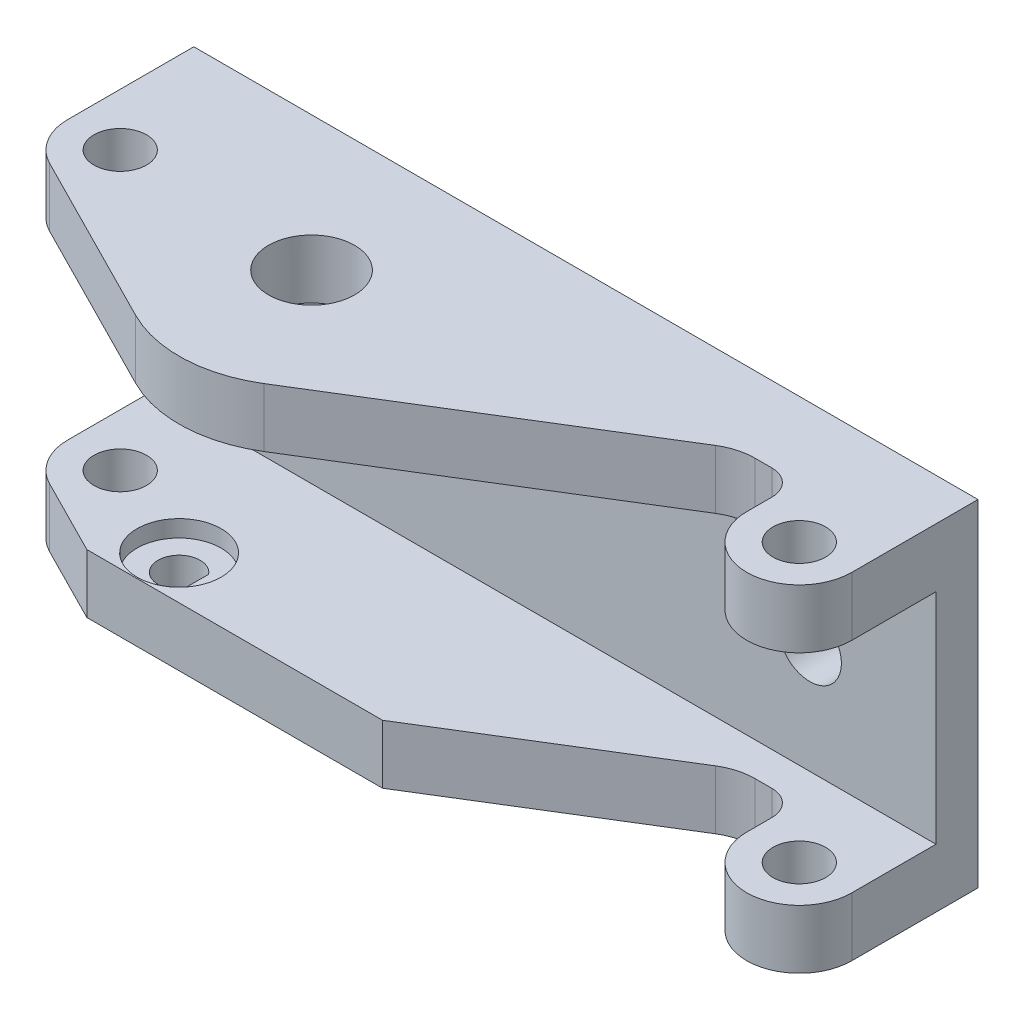
SolidWorks part; units mm, degrees
material "7075-T6 (SN)"
ref_plane "X-Y Datum" through (0, 0, 0) normal (0, 0, 1) x (1, 0, 0)
ref_plane "X-Z Datum" through (0, 0, 0) normal (0, 1, 0) x (1, 0, 0)
ref_plane "Y-Z Datum" through (0, 0, 0) normal (1, 0, 0) x (0, 0, -1)
sketch "Sketch2" plane through (0, 0, 0) normal (1, 0, 0) x (0, 0, -1)
  line L0 (0, -25.4) -> (0, 25.4)
  line L1 (0, 25.4) -> (-63.5, 25.4)
  line L2 (-63.5, 25.4) -> (-63.5, 16.51)
  line L3 (-63.5, 16.51) -> (-6.35, 16.51)
  line L4 (-6.35, 16.51) -> (-6.35, -16.51)
  line L6 (-6.35, 0) -> (0, 0) construction
  line L7 (0, -25.4) -> (-63.5, -25.4)
  line L8 (-63.5, -25.4) -> (-63.5, -16.51)
  line L9 (-63.5, -16.51) -> (-6.35, -16.51)
  dimension "D1" = 16.51
  dimension "D2" = 6.35
  dimension "D3" = 57.15
  dimension "D4" = 8.89
extrude "Boss-Extrude1" add sketch "Sketch2" along normal blind 118.4275
sketch "Sketch3" plane through (0, 0, 0) normal (0, 1, 0) x (1, 0, 0)
  line L0 (0, 0) -> (0, -63.5) construction
  line L1 (118.4275, -6.35) -> (0, -6.35) construction
  line L5 (0, -63.5) -> (0, -19.05)
  line L7 (110.49, -19.05) -> (7.9375, -19.05) construction
  line L9 (118.4275, -63.5) -> (0, -63.5)
  line L10 (118.4275, -63.5) -> (118.4275, -19.05)
  line L12 (110.49, -19.05) -> (118.4275, -19.05) construction
  line L23 (46.1, -39.2459) -> (30.1, -39.2459) construction
  line L24 (30.1, -39.2459) -> (30.1, -31.6259) construction
  line L25 (46.1, -39.2459) -> (46.1, -31.1179) construction
  line L26 (46.1, -31.1179) -> (61.25, -31.1179) construction
  line L27 (61.25, -31.1179) -> (61.25, -9.5221) construction
  line L28 (61.25, -20.32) -> (38.1, -20.32) construction
  line L29 (30.1, -1.3941) -> (30.1, -9.0141) construction
  line L30 (46.1, -1.3941) -> (30.1, -1.3941) construction
  line L31 (46.1, -1.3941) -> (46.1, -9.5221) construction
  line L32 (46.1, -9.5221) -> (61.25, -9.5221) construction
  line L34 (30.7392, -39.5198) -> (4.346, -26.1285)
  line L35 (102.5525, -19.05) -> (102.5525, -15.24)
  line L36 (98.7425, -11.43) -> (96.1828, -11.43)
  line L37 (91.5172, -12.7527) -> (49.3566, -38.747)
  circle A0 centre (7.9375, -19.05) radius 3.9688
  circle A1 centre (110.49, -19.05) radius 3.9688
  circle A3 centre (38.1, -20.32) radius 6.5
  arc A5 (0, -19.05) -> (4.346, -26.1285) centre (7.9375, -19.05) ccw
  arc A7 (102.5525, -19.05) -> (118.4275, -19.05) centre (110.49, -19.05) ccw
  arc A12 (30.1, -31.6259) -> (30.1, -9.0141) centre (38.1, -20.32) cw construction
  arc A13 (91.5172, -12.7527) -> (96.1828, -11.43) centre (96.1828, -20.32) cw
  arc A14 (30.7392, -39.5198) -> (49.3566, -38.747) centre (39.3588, -22.5314) ccw
  arc A15 (98.7425, -11.43) -> (102.5525, -15.24) centre (98.7425, -15.24) cw
  point P15 (38.1, -39.2459)
  point P33 (102.5525, -11.43)
  point P41 (43.4975, -35.56)
  point P42 (93.6625, -11.43)
  point P45 (40.2645, -44.3527)
  point P47 (24.25, -20.32)
  dimension "D1" = 7.9375
  dimension "D2" = 7.9375
  dimension "D6" = 16
  dimension "D10" = 7.9375
  dimension "D11" = 7.9375
  dimension "D7" = 37
  dimension "D13" = 8.128
  dimension "D20" = 49.53
  dimension "D3" = 13
  dimension "D8" = 13.85
  dimension "D21" = 8.89
  dimension "D22" = 19.05
  dimension "D23" = 3.81
  dimension "D4" = 7.9375
  dimension "D5" = 12.7
  dimension "D9" = 38.1
  dimension "D12" = 7.62
  dimension "D14" = 1.27
  dimension "D15" = 7.62
  dimension "D16" = 8.89
  dimension "D17" = 16.51
  dimension "D18" = 35.56
  dimension "D19" = 24.13
extrude "Cut-Extrude1" cut sketch "Sketch3" along normal up to surface (25.4 mm away) up to face at (59.2137, 25.4, 31.75)
sketch "Sketch6" plane through (0, -25.4, 0) normal (0, -1, 0) x (1, 0, 0)
  line L0 (0, 19.05) -> (0, 63.5)
  line L1 (0, 63.5) -> (118.4275, 63.5)
  line L2 (118.4275, 63.5) -> (118.4275, 19.05)
  line L3 (102.5525, 19.05) -> (102.5525, 15.24)
  line L4 (98.7425, 11.43) -> (96.1828, 11.43)
  line L5 (91.5172, 12.7527) -> (60.4199, 31.9258)
  line L6 (60.4199, 31.9258) -> (15.7721, 31.9258)
  line L8 (15.7721, 31.9258) -> (4.346, 26.1285)
  line L9 (25.6667, 27.3709) -> (25.6667, 23.4291)
  circle A0 centre (110.49, 19.05) radius 3.9688
  circle A1 centre (7.9375, 19.05) radius 3.9688
  arc A2 (118.4275, 19.05) -> (102.5525, 19.05) centre (110.49, 19.05) ccw
  arc A3 (102.5525, 15.24) -> (98.7425, 11.43) centre (98.7425, 15.24) cw
  arc A4 (96.1828, 11.43) -> (91.5172, 12.7527) centre (96.1828, 20.32) cw
  arc A5 (4.346, 26.1285) -> (0, 19.05) centre (7.9375, 19.05) ccw
  circle A6 centre (23.1775, 25.4) radius 3.175 construction
  arc A7 (25.6667, 27.3709) -> (25.6667, 23.4291) centre (23.1775, 25.4) ccw
  point P39 (20.0025, 25.4)
  point P40 (25.6667, 25.4)
  dimension "D1" = 7.9375
  dimension "D2" = 6.35
  dimension "D3" = 5.6642
  dimension "D4" = 15.24
  dimension "D5" = 6.35
extrude "Cut-Extrude3" cut sketch "Sketch6" against normal up to surface (8.89 mm away) up to face at (59.2137, -16.51, 34.925)
sketch "Sketch4" plane through (0, 0, 0) normal (0, 0, 1) x (1, 0, 0)
  line L0 (0, -25.4) -> (0, 25.4) construction
  line L1 (118.4275, 16.51) -> (118.4275, -16.51) construction
  circle A0 centre (19.05, 0) radius 4.7625
  circle A1 centre (99.3775, 0) radius 4.7625
  dimension "D1" = 9.525
  dimension "D2" = 19.05
  dimension "D3" = 19.05
extrude "Cut-Extrude2" cut sketch "Sketch4" along normal up to surface (6.35 mm away) up to face at (59.2137, 0, 6.35)
sketch "Sketch7" plane through (0, -16.51, 0) normal (0, 1, 0) x (1, 0, 0)
  circle A0 centre (23.1775, -25.4) radius 6.35
  dimension "D1" = 12.7
extrude "Cut-Extrude4" cut sketch "Sketch7" against normal blind 2.54
